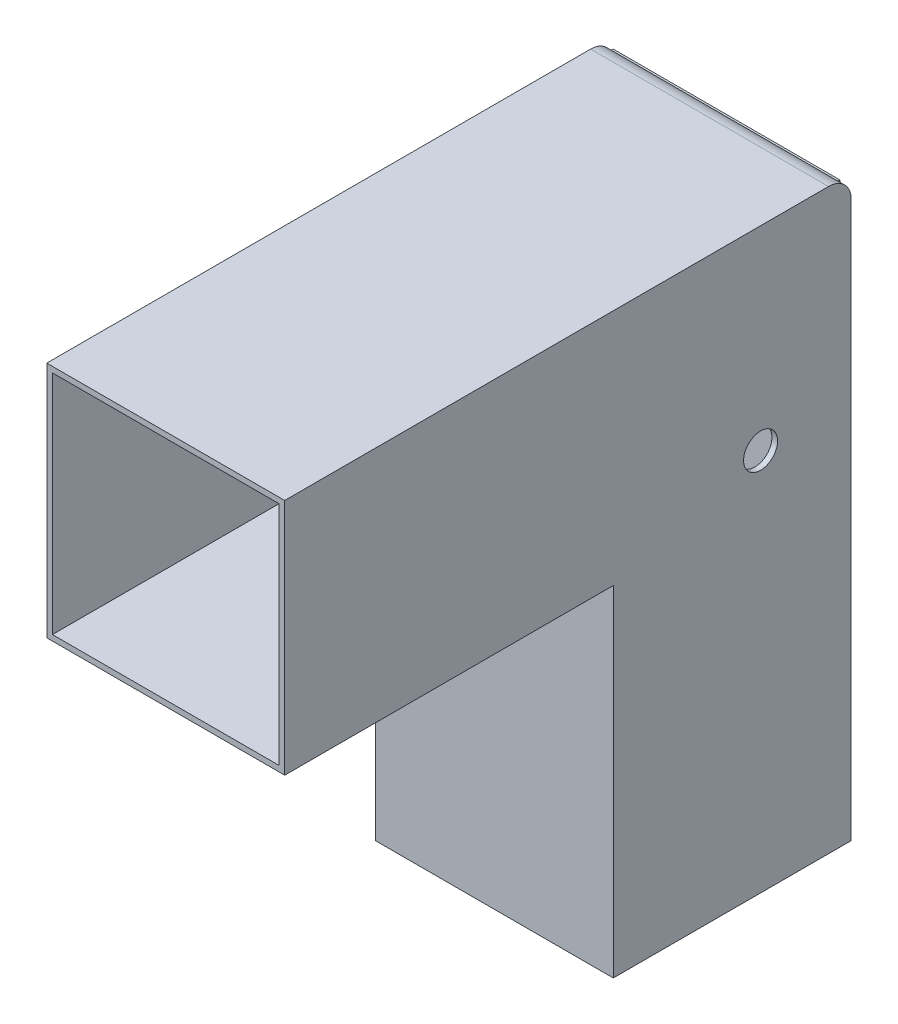
SolidWorks part; units mm, degrees
ref_plane "Plan de face" through (0, 0, 0) normal (0, 0, 1) x (1, 0, 0)
ref_plane "Plan de dessus" through (0, 0, 0) normal (0, 1, 0) x (1, 0, 0)
ref_plane "Plan de droite" through (0, 0, 0) normal (1, 0, 0) x (0, 0, -1)
sketch "Esquisse1" plane through (0, 0, 0) normal (0, 0, 1) x (1, 0, 0)
  line L1 (-10.5, 10.5) -> (10.5, 10.5)
  line L2 (-10.5, 10.5) -> (-10.5, -10.5)
  line L3 (-10.5, -10.5) -> (10.5, -10.5)
  line L4 (10.5, 10.5) -> (10.5, -10.5)
  line L5 (-10.5, 10.5) -> (10.5, -10.5) construction
  line L6 (-10.5, -10.5) -> (10.5, 10.5) construction
  point P0 (0, 0)
  dimension "D1" = 21
  dimension "D2" = 21
extrude "Boss.-Extru.1" add sketch "Esquisse1" along normal blind 50
sketch "Esquisse3" plane through (0, -10.5, 0) normal (0, -1, 0) x (1, 0, 0)
  line L0 (-10.5, 21) -> (10.5, 21)
  line L4 (-10.5, 0) -> (10.5, 0)
  line L5 (10.5, 0) -> (10.5, 50)
  line L6 (10.5, 50) -> (-10.5, 50)
  line L7 (-10.5, 50) -> (-10.5, 0)
  line L8 (-10.5, 0) -> (10.5, 0)
  line L9 (10.5, 0) -> (10.5, 21)
  line L11 (-10.5, 21) -> (-10.5, 0)
  dimension "D2" = 21
  dimension "D1" = 0
extrude "Boss.-Extru.2" add sketch "Esquisse3" along normal blind 30
shell "Coque1" thickness 0.5
fillet "Congé1" radius 2 1 edges at (0, 10.5, 0)
sketch "Esquisse4" plane through (-10.5, 0, 0) normal (-1, 0, 0) x (0, 0, 1)
  circle A0 centre (8, -6.6908) radius 1.5
extrude "Enlèv. mat.-Extru.1" cut sketch "Esquisse4" against normal through all
